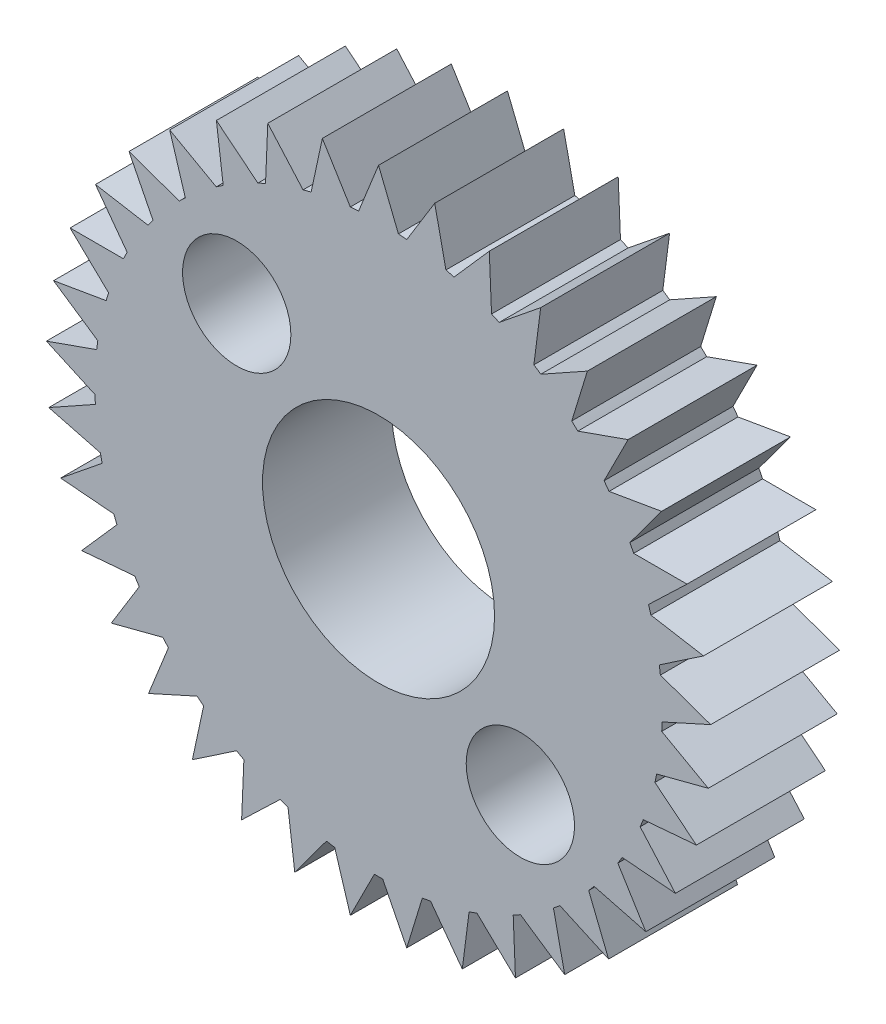
SolidWorks part; units mm, degrees
ref_plane "Plan de face" through (0, 0, 0) normal (0, 0, 1) x (1, 0, 0)
ref_plane "Plan de dessus" through (0, 0, 0) normal (0, 1, 0) x (1, 0, 0)
ref_plane "Plan de droite" through (0, 0, 0) normal (1, 0, 0) x (0, 0, -1)
sketch "Esquisse1" plane through (0, 0, 0) normal (0, 0, 1) x (1, 0, 0)
  line L0 (0, 11) -> (0, -11) construction
  line L1 (0, -11) -> (-11, 0) construction
  line L2 (-11, 0) -> (11, 0) construction
  line L3 (11, 0) -> (0, 11) construction
  line L4 (0, 11) -> (-11, 0) construction
  line L5 (-11, 0) -> (0, -11) construction
  line L6 (0, -11) -> (11, 0) construction
  line L7 (11, 0) -> (5.5, 5.5) construction
  line L8 (5.5, 5.5) -> (-5.5, -5.5) construction
  line L9 (-5.5, -5.5) -> (-5.5, 5.5) construction
  line L10 (-5.5, 5.5) -> (5.5, 5.5) construction
  line L11 (5.5, 5.5) -> (5.5, -5.5) construction
  line L12 (5.5, -5.5) -> (-5.5, -5.5) construction
  circle A0 centre (0, 0) radius 11
  circle A1 centre (0, 0) radius 4.5
  circle A2 centre (-5.5, 5.5) radius 2.1
  circle A3 centre (5.5, -5.5) radius 2.1
  dimension "D1" = 22
  dimension "D2" = 9
  dimension "D3" = 4.2
extrude "Boss.-Extru.1" add sketch "Esquisse1" along normal blind 5
sketch "Esquisse2" plane through (0, 0, 5) normal (0, 0, 1) x (1, 0, 0)
  line L0 (0, 11) -> (0, 12.8927) construction
  line L1 (0, 12.8927) -> (-0.8837, 10.6926)
  line L2 (-0.8837, 10.6926) -> (0.8837, 10.6926)
  line L3 (0.8837, 10.6926) -> (0, 12.8927)
  line L4 (0, 0) -> (0, 11) construction
  circle A0 centre (0, 0) radius 11 construction
  point P9 (0, 0)
  point P11 (0, 10.6926)
  point P12 (0, 9.3482)
  point P13 (0, 12.8927)
  point P14 (-0.8837, 10.6926)
extrude "Boss.-Extru.2" add sketch "Esquisse2" against normal up to surface (5 mm away) up to face at (11, 0, 0)
pattern_circular "Répétition circulaire1" count 37 over 360 about axis through (0, 0, 0) along (0, 0, 1) of "Boss.-Extru.2"
